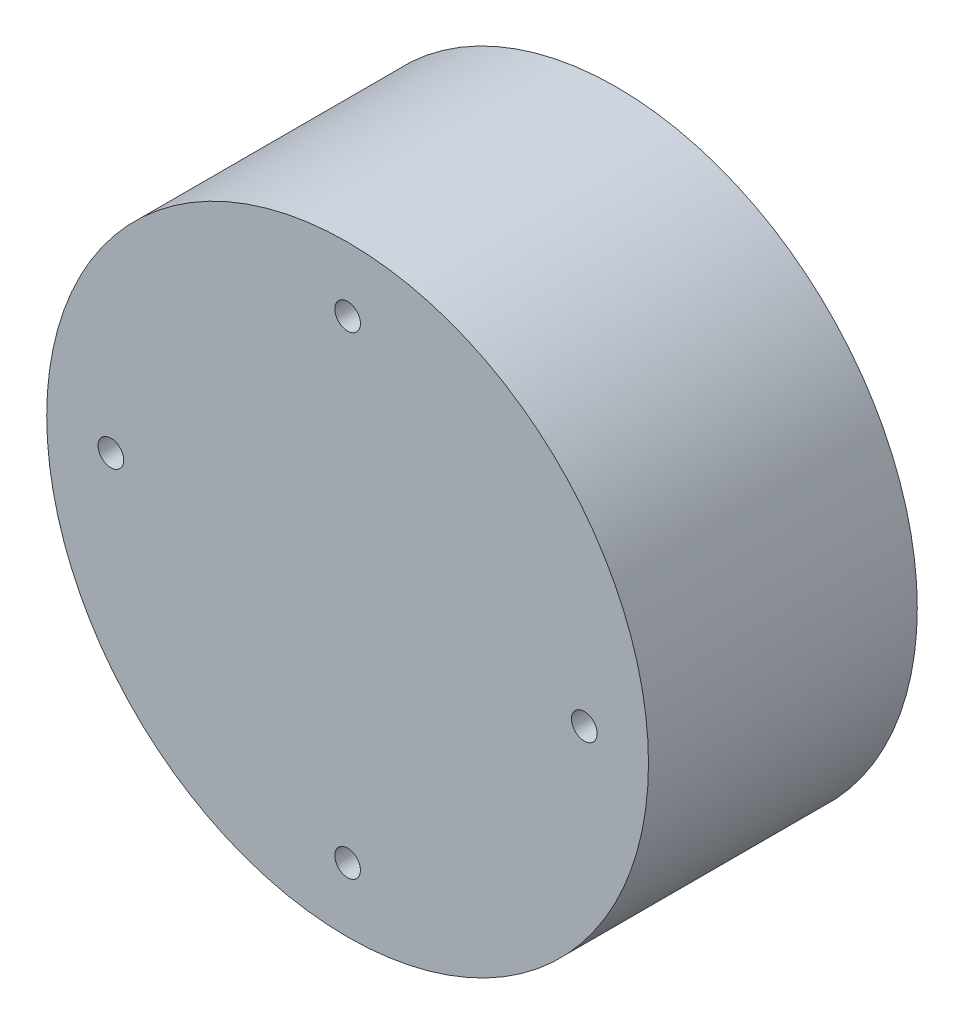
SolidWorks part; units mm, degrees
ref_plane "Plan de face" through (0, 0, 0) normal (0, 0, 1) x (1, 0, 0)
ref_plane "Plan de dessus" through (0, 0, 0) normal (0, 1, 0) x (1, 0, 0)
ref_plane "Plan de droite" through (0, 0, 0) normal (1, 0, 0) x (0, 0, -1)
sketch "Esquisse1" plane through (0, 0, 0) normal (0, 0, 1) x (1, 0, 0)
  circle A0 centre (0, 0) radius 37.5
  dimension "D1" = 75
extrude "Boss.-Extru.1" add sketch "Esquisse1" along normal blind 33.5
sketch "Esquisse2" plane through (0, 0, 33.5) normal (0, 0, 1) x (1, 0, 0)
  line L0 (-37.5, 0) -> (37.5, 0) construction
  line L1 (0, 44.7296) -> (0, -44.9974) construction
  circle A0 centre (0, 0) radius 37.5 construction
  circle A1 centre (0, 29.501) radius 1.6
  circle A2 centre (29.5, 0) radius 1.6
  circle A3 centre (-29.5, 0) radius 1.6
  circle A4 centre (0, -29.501) radius 1.6
  point P2 (0, 0)
  dimension "D1" = 41.72
  dimension "D5" = 3.2
  dimension "D6" = 3.2
  dimension "D7" = 3.2
  dimension "D8" = 3.2
  dimension "D2" = 41.72
  dimension "D3" = 41.72
  dimension "D4" = 59
extrude "Enlèv. mat.-Extru.1" cut sketch "Esquisse2" against normal through all
